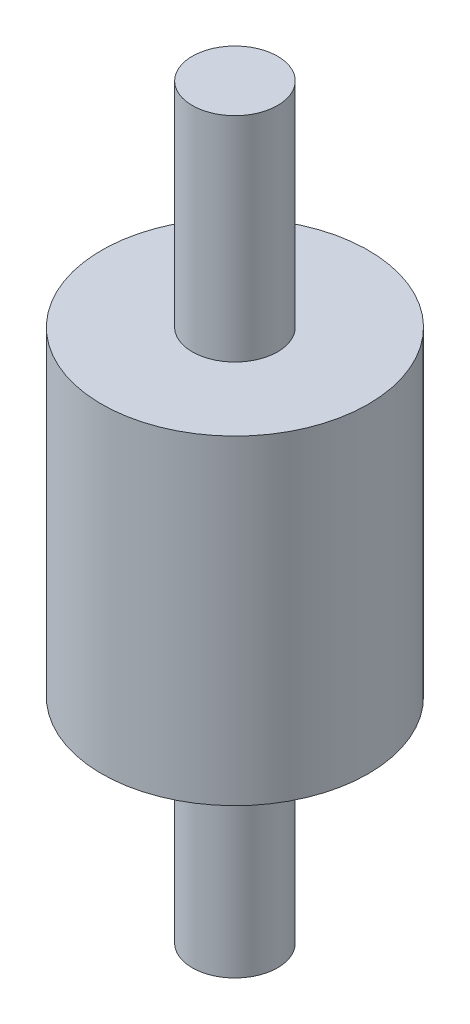
SolidWorks part; units mm, degrees
ref_plane "Front Plane" through (0, 0, 0) normal (0, 0, 1) x (1, 0, 0)
ref_plane "Top Plane" through (0, 0, 0) normal (0, 1, 0) x (1, 0, 0)
ref_plane "Right Plane" through (0, 0, 0) normal (1, 0, 0) x (0, 0, -1)
sketch "Sketch1" plane through (0, 0, 0) normal (0, 0, 1) x (1, 0, 0)
  line L0 (0, 70) -> (-4, 70)
  line L1 (-4, 70) -> (-4, 50)
  line L2 (-4, 50) -> (-12.5, 50)
  line L3 (-12.5, 50) -> (-12.5, 20)
  line L4 (-12.5, 20) -> (-4, 20)
  line L5 (-4, 20) -> (-4, 0)
  line L6 (-4, 0) -> (0, 0)
  line L7 (0, 0) -> (0, 70)
  dimension "D1" = 4
  dimension "D2" = 20
  dimension "D3" = 20
  dimension "D4" = 30
  dimension "D5" = 12.5
revolve "Revolve1" add sketch "Sketch1" angle 360 about L7
